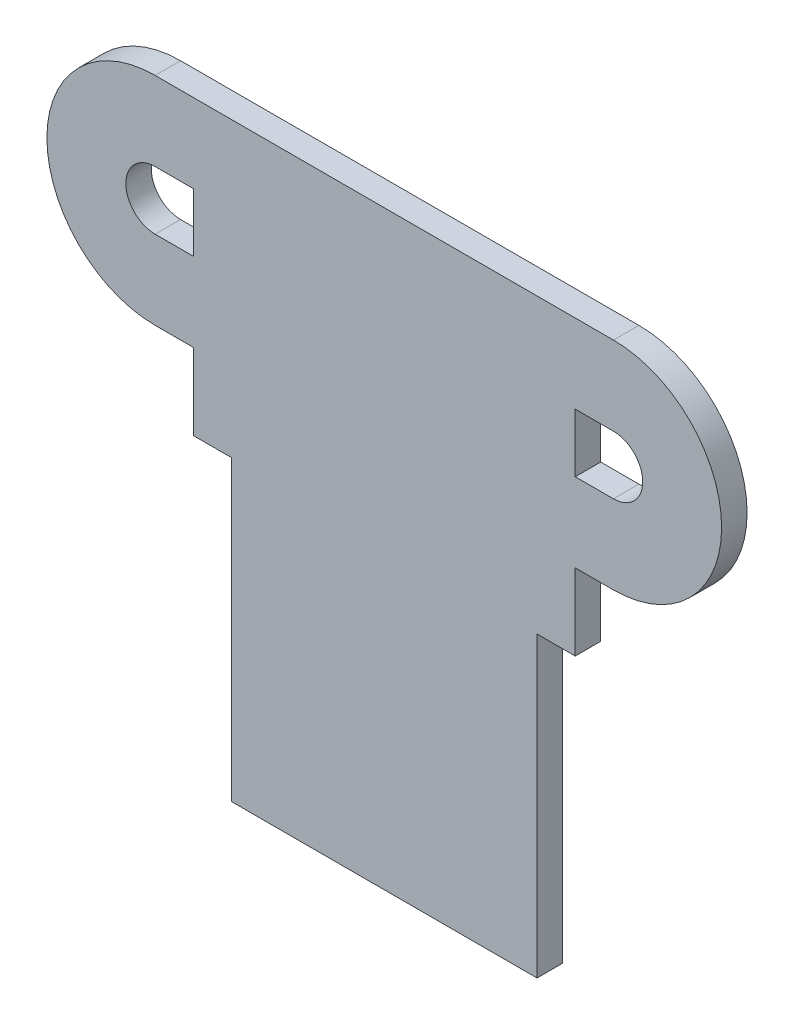
SolidWorks part; units mm, degrees
material "ABS"
ref_plane "Plan de face" through (0, 0, 0) normal (0, 0, 1) x (1, 0, 0)
ref_plane "Plan de dessus" through (0, 0, 0) normal (0, 1, 0) x (1, 0, 0)
ref_plane "Plan de droite" through (0, 0, 0) normal (1, 0, 0) x (0, 0, -1)
sketch "Esquisse1" plane through (0, 0, 0) normal (0, 0, 1) x (1, 0, 0)
  line L0 (12, 11.7) -> (13.5, 11.7)
  line L1 (0, 0) -> (12, 0)
  line L2 (0, 0) -> (0, 11.7)
  line L3 (-3, 14.7) -> (-1.5, 14.7)
  line L4 (12, 0) -> (12, 11.7)
  line L5 (-1.5, 11.7) -> (0, 11.7)
  line L6 (-1.5, 14.7) -> (-1.5, 11.7)
  line L7 (-3, 23.2) -> (15, 23.2)
  line L8 (13.5, 11.7) -> (13.5, 14.7)
  line L9 (13.5, 14.7) -> (15, 14.7)
  line L10 (15, 20.1) -> (13.5, 20.1)
  line L11 (13.5, 20.1) -> (13.5, 17.8)
  line L12 (13.5, 17.8) -> (15, 17.8)
  line L13 (-3, 20.1) -> (-1.5, 20.1)
  line L14 (-1.5, 20.1) -> (-1.5, 17.8)
  line L15 (-1.5, 17.8) -> (-3, 17.8)
  arc A0 (-3, 23.2) -> (-3, 14.7) centre (-3, 18.95) ccw
  arc A1 (15, 23.2) -> (15, 14.7) centre (15, 18.95) cw
  arc A2 (15, 20.1) -> (15, 17.8) centre (15, 18.95) cw
  arc A3 (-3, 20.1) -> (-3, 17.8) centre (-3, 18.95) ccw
  dimension "D8" = 1.5
  dimension "D2" = 3.1
  dimension "D13" = 3.1
  dimension "D1" = 18
  dimension "D3" = 11.7
  dimension "D4" = 12
  dimension "D5" = 1.5
  dimension "D6" = 8.5
  dimension "D7" = 1.5
  dimension "D9" = 3
  dimension "D10" = 3
  dimension "D11" = 1.5
  dimension "D12" = 1.5
  dimension "D14" = 1.5
  dimension "D15" = 1.5
extrude "Boss.-Extru.1" add sketch "Esquisse1" along normal blind 1
